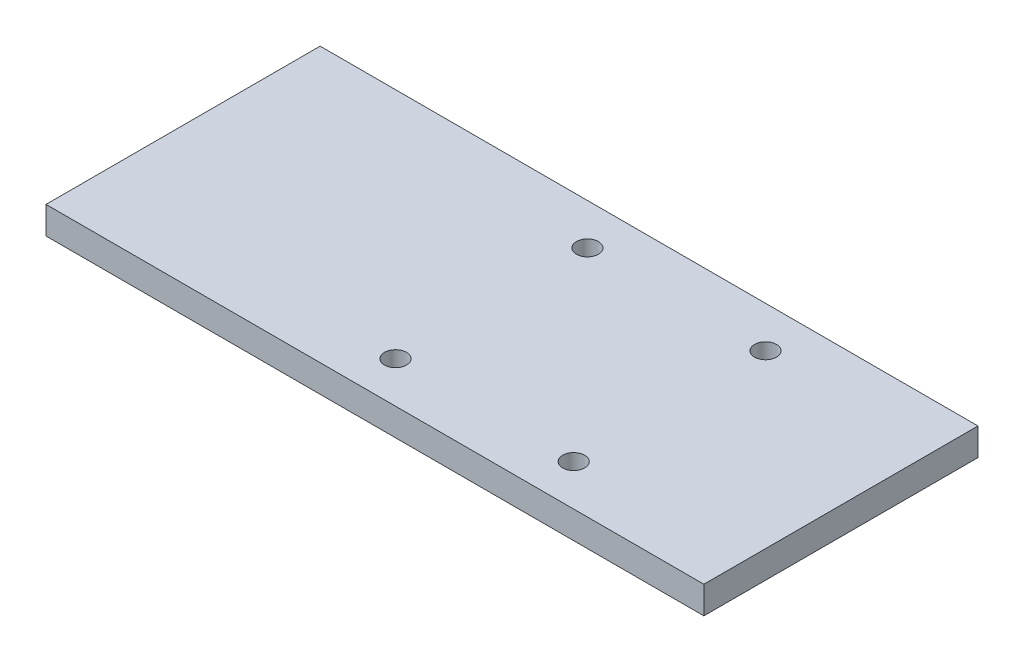
SolidWorks part; units mm, degrees
ref_plane "Front Plane" through (0, 0, 0) normal (0, 0, 1) x (1, 0, 0)
ref_plane "Top Plane" through (0, 0, 0) normal (0, 1, 0) x (1, 0, 0)
ref_plane "Right Plane" through (0, 0, 0) normal (1, 0, 0) x (0, 0, -1)
sketch "Sketch1" plane through (0, 0, 0) normal (1, 0, 0) x (0, 0, -1)
  line L1 (-31.75, 3.175) -> (31.75, 3.175)
  line L2 (-31.75, 3.175) -> (-31.75, -3.175)
  line L3 (-31.75, -3.175) -> (31.75, -3.175)
  line L4 (31.75, 3.175) -> (31.75, -3.175)
  line L5 (-31.75, 3.175) -> (31.75, -3.175) construction
  line L6 (-31.75, -3.175) -> (31.75, 3.175) construction
  point P0 (0, 0)
  dimension "D1" = 63.5
  dimension "D2" = 6.35
extrude "Boss-Extrude1" add sketch "Sketch1" along normal mid plane 152.4
hole_wizard "#10 Clearance Hole1" positions "Sketch3" profile "Sketch2" hole size "#10" standard "ANSI Inch"
sketch "Sketch3" plane through (0, 3.175, 0) normal (0, 1, 0) x (1, 0, 0)
  line L1 (-4.7625, 22.225) -> (36.5125, 22.225) construction
  line L2 (-4.7625, 22.225) -> (-4.7625, -22.225) construction
  line L3 (-4.7625, -22.225) -> (36.5125, -22.225) construction
  line L4 (36.5125, 22.225) -> (36.5125, -22.225) construction
  line L6 (-4.7625, 22.225) -> (36.5125, -22.225) construction
  line L7 (15.875, 0) -> (76.2, 0) construction
  line L8 (76.2, 31.75) -> (76.2, -31.75) construction
  point P0 (-4.7625, 22.225)
  point P1 (36.5125, -22.225)
  point P238 (-4.7625, -22.225)
  point P239 (36.5125, 22.225)
  dimension "D1" = 41.275
  dimension "D2" = 44.45
  dimension "D3" = 60.325
sketch "Sketch2" plane through (-4.7625, 3.175, -22.225) normal (1, 0, 0) x (0, 0, 1)
  line L0 (0, 0) -> (0, 11.1858)
  line L1 (0, 11.1858) -> (2.5527, 9.652)
  line L2 (2.5527, 9.652) -> (2.5527, 0)
  line L5 (2.5527, 0) -> (0, 0)
  line L10 (0, 11.1858) -> (-2.5527, 9.652) construction
  line L11 (0, -6.35) -> (0, 107.95) construction
  dimension "Hole Dia." = 5.1054
  dimension "Hole Depth" = 9.652
  dimension "Drill Angle" = 118
